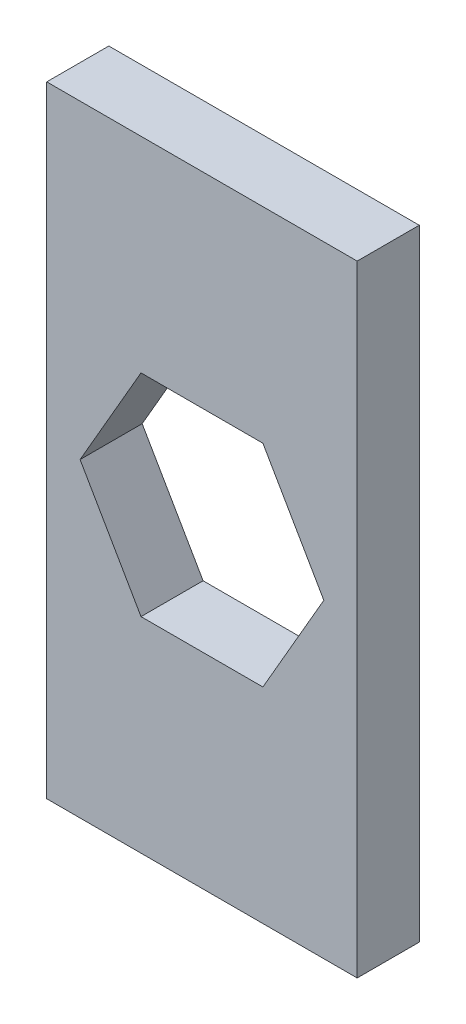
SolidWorks part; units mm, degrees
ref_plane "Front Plane" through (0, 0, 0) normal (0, 0, 1) x (1, 0, 0)
ref_plane "Top Plane" through (0, 0, 0) normal (0, 1, 0) x (1, 0, 0)
ref_plane "Right Plane" through (0, 0, 0) normal (1, 0, 0) x (0, 0, -1)
sketch "Sketch1" plane through (0, 0, 0) normal (0, 0, 1) x (1, 0, 0)
  line L1 (0, 0) -> (10, 0)
  line L2 (0, 0) -> (0, 20)
  line L3 (0, 20) -> (10, 20)
  line L4 (10, 0) -> (10, 20)
  line L5 (6.963, 6.6) -> (8.926, 10)
  line L6 (8.926, 10) -> (6.963, 13.4)
  line L7 (6.963, 13.4) -> (3.037, 13.4)
  line L8 (3.037, 13.4) -> (1.074, 10)
  line L9 (1.074, 10) -> (3.037, 6.6)
  line L10 (3.037, 6.6) -> (6.963, 6.6)
  circle A0 centre (5, 10) radius 3.4 construction
  dimension "D1" = 10
  dimension "D2" = 20
  dimension "D3" = 6.8
  dimension "D4" = 10
  dimension "D5" = 5
extrude "Boss-Extrude1" add sketch "Sketch1" along normal blind 2
